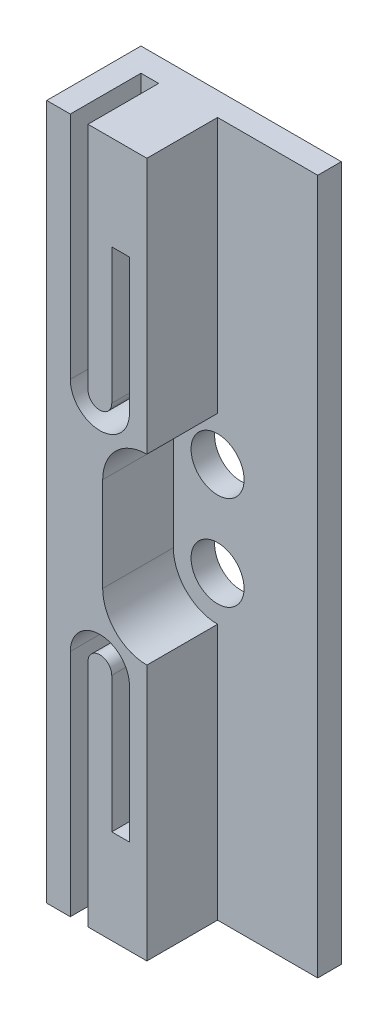
SolidWorks part; units mm, degrees
ref_plane "Plan de face" through (0, 0, 0) normal (0, 0, 1) x (1, 0, 0)
ref_plane "Plan de dessus" through (0, 0, 0) normal (0, 1, 0) x (1, 0, 0)
ref_plane "Plan de droite" through (0, 0, 0) normal (1, 0, 0) x (0, 0, -1)
sketch "Esquisse1" plane through (0, 0, 0) normal (0, 0, 1) x (1, 0, 0)
  line L1 (0, 0) -> (17, 0)
  line L2 (0, 0) -> (0, -59)
  line L3 (0, -59) -> (17, -59)
  line L4 (17, 0) -> (17, -59)
  dimension "D1" = 17
  dimension "D2" = 59
extrude "Boss.-Extru.1" add sketch "Esquisse1" along normal blind 2
sketch "Esquisse2" plane through (0, 0, 2) normal (0, 0, 1) x (1, 0, 0)
  line L0 (0, -59) -> (17, -59) construction
  line L1 (0, 0) -> (8.5, 0)
  line L2 (0, 0) -> (0, -59)
  line L3 (0, -59) -> (8.5, -59)
  line L4 (8.5, 0) -> (8.5, -59)
extrude "Boss.-Extru.2" add sketch "Esquisse2" along normal blind 6
sketch "Esquisse3" plane through (0, 0, 8) normal (0, 0, 1) x (1, 0, 0)
  line L0 (0, -59) -> (8.5, -59) construction
  line L1 (2, -59) -> (3.5, -59)
  line L2 (2, -59) -> (2, 0)
  line L3 (2, 0) -> (3.5, 0)
  line L4 (3.5, -59) -> (3.5, 0)
  line L5 (8.5, 0) -> (0, 0) construction
  line L6 (8.5, -59) -> (8.5, 0) construction
  line L7 (2, -19.5) -> (3.5, -19.5)
  line L8 (5.5199, -51) -> (7.0199, -51)
  line L9 (5.5199, -51) -> (5.5199, -8)
  line L10 (5.5199, -8) -> (7.0199, -8)
  line L11 (7.0199, -51) -> (7.0199, -8)
  line L13 (3.5, -19.5) -> (5.5199, -19.5)
  line L14 (5.5199, -19.5) -> (7.0908, -19.5)
  line L15 (2, -39.5) -> (3.5, -39.5)
  line L16 (3.5, -39.5) -> (5.5199, -39.5)
  line L17 (5.5199, -39.5) -> (7.0199, -39.5)
  arc A0 (2, -19.5) -> (7.0199, -19.5) centre (4.51, -19.5) ccw
  arc A1 (3.5, -19.5) -> (5.5199, -19.5) centre (4.51, -19.5) ccw
  arc A2 (3.5, -39.5) -> (5.5199, -39.5) centre (4.51, -39.5) cw
  arc A3 (2, -39.5) -> (7.0199, -39.5) centre (4.51, -39.5) cw
  point P14 (6.2699, -8)
  line M10 (0, -59) -> (8.5, -59)
  line M12 (8.5, 0) -> (0, 0)
  dimension "D1" = 1.5
  dimension "D2" = 5
  dimension "D3" = 1.5
  dimension "D4" = 8
  dimension "D5" = 8
  dimension "D6" = 20
  dimension "D7" = 11.5
  dimension "D8" = 11.5
extrude "Enlèv. mat.-Extru.1" cut sketch "Esquisse3" against normal blind 6 contours L15 L2 L4 M10 | A3 L15 L4 | A3 L4 A2 L9 | A3 L9 L17 | L17 L9 L8 L11 | L9 L14 L11 L10 | L2 L7 L4 M12 | L7 A0 L4 | A1 L4 A0 L9 | L9 A0 L14
sketch "Esquisse4" plane through (0, 0, 8) normal (0, 0, 1) x (1, 0, 0)
  line L2 (3.5, -59) -> (8.5, -59) construction
  line L3 (17, -59) -> (17, 0) construction
  line L4 (0, 0) -> (0, -59) construction
  circle A0 centre (8.5, -33.5) radius 2.25
  circle A1 centre (8.5, -25.5) radius 2.25
  point P8 (6, -59)
  dimension "D1" = 4.5
  dimension "D2" = 4.5
  dimension "D3" = 8
  dimension "D4" = 25.5
  dimension "D5" = 17
  dimension "D6" = 8.5
  dimension "D7" = 8.5
extrude "Enlèv. mat.-Extru.2" cut sketch "Esquisse4" against normal blind 14
sketch "Esquisse5" plane through (0, 0, 8) normal (0, 0, 1) x (1, 0, 0)
  line L0 (4.75, -33.5) -> (4.75, -25.5)
  circle A0 centre (8.5, -25.5) radius 3.75
  circle A1 centre (8.5, -33.5) radius 3.75
  arc M1 (8.5, -27.75) -> (8.5, -23.25) centre (8.5, -25.5) cw
  line M2 (8.5, -23.25) -> (8.5, 0)
  line M22 (8.5, -59) -> (8.5, -35.75)
  arc M23 (8.5, -35.75) -> (8.5, -31.25) centre (8.5, -33.5) cw
  line M24 (8.5, -31.25) -> (8.5, -27.75)
  dimension "D1" = 7.5
  dimension "D2" = 7.5
extrude "Enlèv. mat.-Extru.3" cut sketch "Esquisse5" against normal blind 6 contours A1 A0 L0 M24 | A0 M2 M24 M1 | A1 M24 M22 M23
